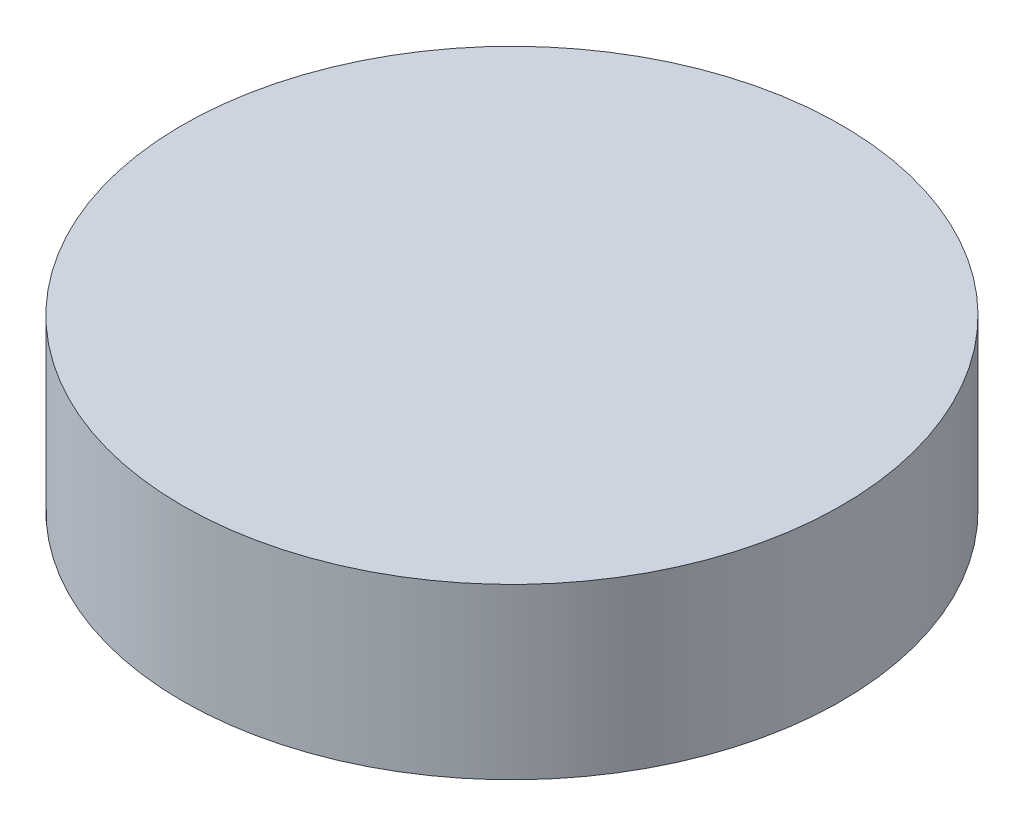
SolidWorks part; units mm, degrees
ref_plane "Front Plane" through (0, 0, 0) normal (0, 0, 1) x (1, 0, 0)
ref_plane "Top Plane" through (0, 0, 0) normal (0, 1, 0) x (1, 0, 0)
ref_plane "Right Plane" through (0, 0, 0) normal (1, 0, 0) x (0, 0, -1)
sketch "Sketch1" plane through (0, 0, 0) normal (0, 1, 0) x (1, 0, 0)
  circle A0 centre (0, 0) radius 9.35
  dimension "D1" = 18.7
extrude "Boss-Extrude1" add sketch "Sketch1" along normal blind 4.8
sketch "Sketch2" plane through (0, 4.8, 0) normal (0, 1, 0) x (1, 0, 0)
  circle A0 centre (0, 0) radius 8.1
  dimension "D1" = 16.2
extrude "Cut-Extrude1" cut sketch "Sketch2" against normal through all from offset 0.3 offset against normal yes
